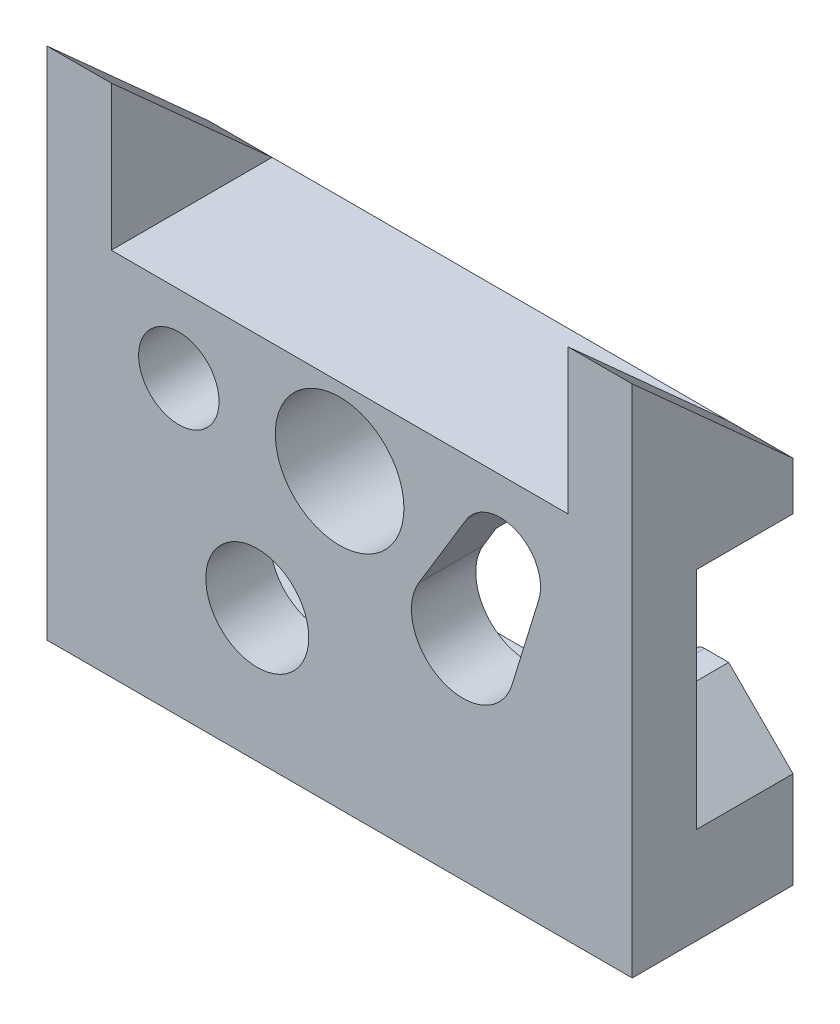
SolidWorks part; units mm, degrees
ref_plane "Front Plane" through (0, 0, 0) normal (0, 0, 1) x (1, 0, 0)
ref_plane "Top Plane" through (0, 0, 0) normal (0, 1, 0) x (1, 0, 0)
ref_plane "Right Plane" through (0, 0, 0) normal (1, 0, 0) x (0, 0, -1)
ref_plane "Switch Base" through (0, 0, -4) normal (0, 0, 1) x (1, 0, 0)
ref_plane "Plane2" through (0, 0, -6) normal (0, 0, 1) x (1, 0, 0)
sketch "Outside Frame" plane through (0, 0, -4) normal (0, 0, 1) x (1, 0, 0)
  line L1 (9.1, -9.1) -> (-9.1, -9.1)
  line L2 (9.1, -9.1) -> (9.1, 9.1)
  line L3 (9.1, 9.1) -> (-9.1, 9.1)
  line L4 (-9.1, -9.1) -> (-9.1, 9.1)
  line L5 (9.1, -9.1) -> (-9.1, 9.1) construction
  line L6 (9.1, 9.1) -> (-9.1, -9.1) construction
  line L7 (7.1, -7.1) -> (-7.1, -7.1)
  line L8 (7.1, -7.1) -> (7.1, 7.1)
  line L9 (7.1, 7.1) -> (-7.1, 7.1)
  line L10 (-7.1, -7.1) -> (-7.1, 7.1)
  line L11 (7.1, -7.1) -> (-7.1, 7.1) construction
  line L12 (7.1, 7.1) -> (-7.1, -7.1) construction
  point P0 (0, 0)
  point P5 (0, 0)
  dimension "D1" = 14.2
  dimension "D2" = 2
extrude "Outer Frame Extrude" add sketch "Outside Frame" along normal blind 4 and the other way blind 2 separate body
sketch "Switch Pin Holes" plane through (0, 0, -4) normal (0, 0, 1) x (1, 0, 0)
  line L0 (5, 0) -> (-5, 0) construction
  circle A0 centre (0, 0) radius 2
  circle A1 centre (-5, 0) radius 1.25
  circle A2 centre (5, 0) radius 1.25
  point P12 (0, 0)
  dimension "D1" = 4
  dimension "D3" = 2.5
  dimension "D2" = 10
sketch "Hotswap Well" plane through (0, 0, -6) normal (0, 0, -1) x (-1, 0, 0)
  line L0 (-10, -1.1) -> (-2.3558, -1.1)
  line L2 (0, -2.6) -> (5, -2.6)
  line L3 (5, -2.6) -> (5, -3.35)
  line L4 (5, -3.35) -> (10, -3.35)
  line L5 (10, -3.35) -> (10, -6.9)
  line L6 (10, -6.9) -> (-6, -6.9)
  line L7 (-6, -6.9) -> (-6, -4.1)
  line L8 (-6, -4.1) -> (-10, -4.1)
  line L9 (-10, -4.1) -> (-10, -1.1)
  line L10 (0, 0) -> (0, -9.97) construction
  line L11 (-10, -2.6) -> (0, -2.6) construction
  line L12 (0, -2.6) -> (10, -2.6) construction
  line L13 (10, -2.6) -> (10, -3.35) construction
  arc A0 (-2.3558, -1.1) -> (0, -2.6) centre (0, 0) ccw
  circle A1 centre (0, 0) radius 2 construction
  dimension "D5" = 4.3
  dimension "D1" = 3
  dimension "D2" = 20
  dimension "D3" = 6
  dimension "D4" = 2.6
  dimension "D6" = 5
  dimension "D7" = 0.75
sketch "Hotswap Holes" plane through (0, 0, 0) normal (0, 0, 1) x (1, 0, 0)
  line L0 (10, -2.6) -> (0, -2.6) construction
  line L1 (3.9309, 0.6477) -> (2.4655, -1.7709)
  line L2 (5.3632, -3.0705) -> (6.1947, -0.3676)
  circle A0 centre (-2.5601, -4.9653) radius 1.6
  arc A1 (4.5122, -1.1509) -> (4.4649, -1.1297) centre (3.8339, -2.6) ccw
  circle A2 centre (5, 0) radius 1.25 construction
  arc A3 (6.1947, -0.3676) -> (3.9309, 0.6477) centre (5, 0) ccw
  arc A4 (4.4649, -1.1297) -> (4.5122, -1.1509) centre (5, 0) ccw
  arc A5 (2.4655, -1.7709) -> (5.3632, -3.0705) centre (3.8339, -2.6) ccw
  dimension "D1" = 3.2
sketch "Hotswap Base" plane through (0, 0, -4) normal (0, 0, 1) x (1, 0, 0)
  line L0 (-9.1, 9.1) -> (-9.1, -9.1) construction
  line L1 (-9.1, 2.4) -> (9.1, 2.4)
  line L2 (-9.1, 2.4) -> (-9.1, -9.1)
  line L3 (-9.1, -9.1) -> (9.1, -9.1)
  line L4 (9.1, 2.4) -> (9.1, -9.1)
  dimension "D1" = 11.5
extrude "Hotswap Base Block" add sketch "Hotswap Base" against normal blind 5
sketch "Sketch1" plane through (0, 0, 0) normal (1, 0, 0) x (0, 0, -1)
  line L0 (4, 10.01) -> (4, -10.01) construction
  line L1 (4, 9.1) -> (6, 9.1)
  line L2 (4, 9.1) -> (4, 2.4)
  line L3 (4, 2.4) -> (6, 2.4)
  line L4 (6, 9.1) -> (6, 2.4)
  line L5 (6, 9.1) -> (0, 9.1) construction
  line L6 (6, 10.01) -> (6, -10.01) construction
  line L7 (9, 2.4) -> (6, 2.4) construction
extrude "Cut-Extrude4" cut sketch "Sketch1" against normal through all both and the other way through all
extrude "Cut-Extrude1" cut sketch "Hotswap Well" along normal blind 4
extrude "Switch Holes" cut sketch "Switch Pin Holes" against normal offset from surface (4 mm away) 1 up to face at (-0.9282, -1.2054, -9)
extrude "Cut-Extrude3" cut sketch "Hotswap Holes" against normal up to surface (8 mm away) contours L2 A3 L1 A5 | A0 up to face at (5, 0.075, -8)
chamfer "Chamfer1" distance 2 angle 45 4 edges at (9.1, -1.1, -7.5) (9.1, -4.1, -7.5) (-9.1, -6.9, -7.5) (-9.1, -3.35, -7.5)
chamfer "Chamfer2" distance 4.5 angle 48 2 edges at (-8.1, 2.4, -4) (8.1, 2.4, -4)
fillet "Fillet1" radius 0.35 5 edges at (2.3558, -1.1, -7.5) (-5, -3.35, -7.5) (-5, -2.6, -7.5) (6, -6.9, -7.5) (6, -4.1, -7.5)
split "Split1" trim tools "Switch Base" bodies to split 107 resulting bodies 110
